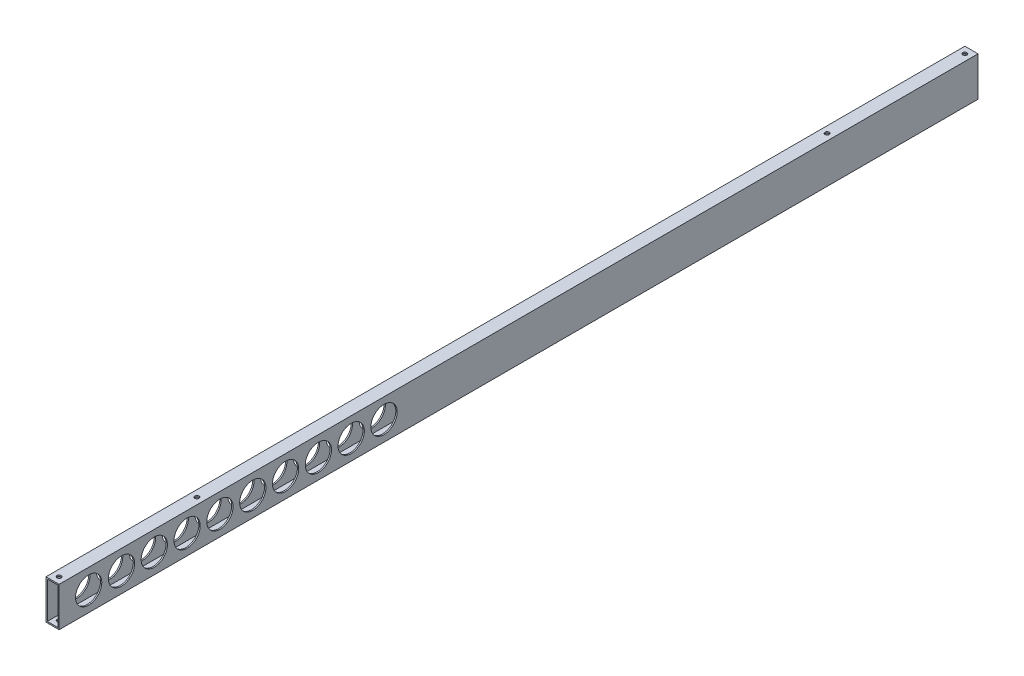
SolidWorks part; units mm, degrees
material "6061 合金"
ref_plane "正面" through (0, 0, 0) normal (0, 0, 1) x (1, 0, 0)
ref_plane "平面" through (0, 0, 0) normal (0, 1, 0) x (1, 0, 0)
ref_plane "右側面" through (0, 0, 0) normal (1, 0, 0) x (0, 0, -1)
sketch "ｽｹｯﾁ1" plane through (0, 0, 0) normal (0, 0, 1) x (1, 0, 0)
  line L1 (5, -15) -> (-5, -15)
  line L2 (5, -15) -> (5, 15)
  line L3 (5, 15) -> (-5, 15)
  line L4 (-5, -15) -> (-5, 15)
  line L5 (5, -15) -> (-5, 15) construction
  line L6 (5, 15) -> (-5, -15) construction
  point P0 (0, 0)
  dimension "D1" = 10
  dimension "D2" = 30
extrude "押し出し-薄板1" add sketch "ｽｹｯﾁ1" along normal blind 700 thin
sketch "ｽｹｯﾁ2" plane through (0, 15, 0) normal (0, 1, 0) x (1, 0, 0)
  line L0 (0, -700) -> (0, 0) construction
  line L1 (5, -700) -> (-5, -700) construction
  line L2 (5, 0) -> (-5, 0) construction
  line L3 (-5, -350) -> (5, -350) construction
  line L4 (-5, -700) -> (-5, 0) construction
  line L5 (5, -700) -> (5, 0) construction
  circle A0 centre (0, -5) radius 1.6
  circle A1 centre (0, -110) radius 1.6
  circle A2 centre (0, -695) radius 1.6
  circle A3 centre (0, -590) radius 1.6
  dimension "D1" = 5
  dimension "D2" = 105
  dimension "D3" = 3.2
extrude "ｶｯﾄ - 押し出し1" cut sketch "ｽｹｯﾁ2" against normal through all
sketch "ｽｹｯﾁ3" plane through (5, 0, 0) normal (1, 0, 0) x (0, 0, -1)
  line L0 (-700, 0) -> (0, 0) construction
  line L1 (-700, -15) -> (-700, 15) construction
  line L2 (0, -15) -> (0, 15) construction
  circle A0 centre (-677.5, 0) radius 10
  circle A1 centre (-652.5, 0) radius 10
  circle A2 centre (-627.5, 0) radius 10
  circle A3 centre (-602.5, 0) radius 10
  circle A4 centre (-577.5, 0) radius 10
  circle A5 centre (-552.5, 0) radius 10
  circle A6 centre (-527.5, 0) radius 10
  circle A7 centre (-502.5, 0) radius 10
  circle A8 centre (-477.5, 0) radius 10
  circle A9 centre (-452.5, 0) radius 10
  dimension "D1" = 20
  dimension "D2" = 22.5
  dimension "D4" = 25
  dimension "D3" = 10
extrude "ｶｯﾄ - 押し出し2" cut sketch "ｽｹｯﾁ3" against normal through all
